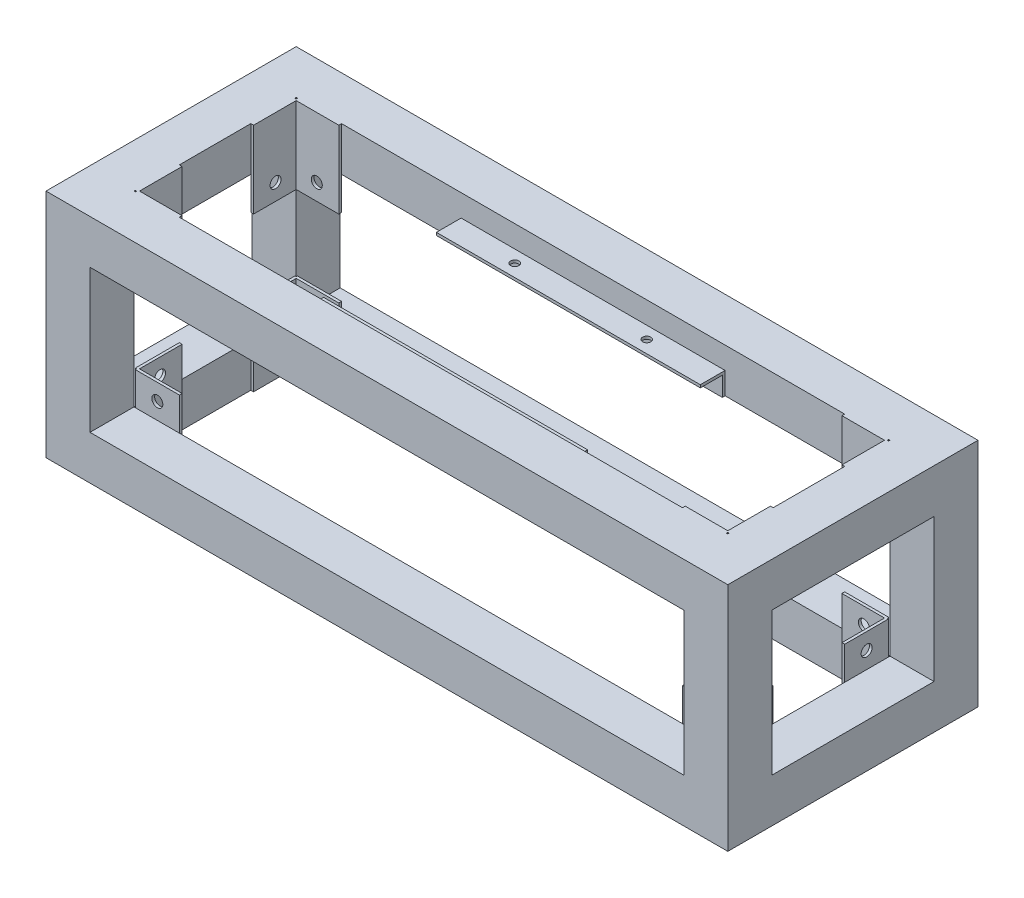
SolidWorks part; units mm, degrees
ref_plane "Front Plane" through (0, 0, 0) normal (0, 0, 1) x (1, 0, 0)
ref_plane "Top Plane" through (0, 0, 0) normal (0, 1, 0) x (1, 0, 0)
ref_plane "Right Plane" through (0, 0, 0) normal (1, 0, 0) x (0, 0, -1)
sketch "Sketch1" plane through (0, 0, 0) normal (0, 1, 0) x (1, 0, 0)
  line L1 (-196.85, 72.2313) -> (196.85, 72.2312)
  line L2 (-196.85, 72.2313) -> (-196.85, -72.2313)
  line L3 (-196.85, -72.2313) -> (196.85, -72.2313)
  line L4 (196.85, 72.2312) -> (196.85, -72.2313)
  line L5 (-196.85, 72.2313) -> (196.85, -72.2313) construction
  line L6 (-196.85, -72.2313) -> (196.85, 72.2312) construction
  point P0 (0, 0)
  dimension "D1" = 393.7
  dimension "D2" = 144.4625
extrude "Boss-Extrude1" add sketch "Sketch1" along normal blind 133.35
sketch "Sketch6" plane through (0, 0, 72.2313) normal (0, 0, 1) x (1, 0, 0)
  line L8 (-171.45, 25.4) -> (171.45, 25.4)
  line L9 (171.45, 25.4) -> (171.45, 107.95)
  line L10 (171.45, 107.95) -> (-171.45, 107.95)
  line L11 (-171.45, 107.95) -> (-171.45, 25.4)
  line L12 (-171.45, 25.4) -> (171.45, 25.4)
  line L13 (171.45, 25.4) -> (171.45, 107.95)
  line L14 (171.45, 107.95) -> (-171.45, 107.95)
  line L15 (-171.45, 107.95) -> (-171.45, 25.4)
  dimension "D1" = 25.4
extrude "Cut-Extrude4" cut sketch "Sketch6" against normal through all
sketch "Sketch7" plane through (-196.85, 0, 0) normal (-1, 0, 0) x (0, 0, 1)
  line L8 (-46.8312, 25.4) -> (46.8313, 25.4)
  line L9 (46.8313, 25.4) -> (46.8313, 107.95)
  line L10 (46.8313, 107.95) -> (-46.8312, 107.95)
  line L11 (-46.8312, 107.95) -> (-46.8312, 25.4)
  line L12 (-46.8312, 25.4) -> (46.8313, 25.4)
  line L13 (46.8313, 25.4) -> (46.8313, 107.95)
  line L14 (46.8313, 107.95) -> (-46.8312, 107.95)
  line L15 (-46.8312, 107.95) -> (-46.8312, 25.4)
  dimension "D1" = 25.4
extrude "Cut-Extrude5" cut sketch "Sketch7" against normal through all
sketch "Sketch8" plane through (0, 133.35, 0) normal (0, 1, 0) x (1, 0, 0)
  line L8 (171.45, -46.8313) -> (171.45, 46.8312)
  line L9 (171.45, 46.8312) -> (-171.45, 46.8312)
  line L10 (-171.45, 46.8312) -> (-171.45, -46.8313)
  line L11 (-171.45, -46.8313) -> (171.45, -46.8313)
  line L12 (171.45, -46.8313) -> (171.45, 46.8312)
  line L13 (171.45, 46.8312) -> (-171.45, 46.8312)
  line L14 (-171.45, 46.8312) -> (-171.45, -46.8313)
  line L15 (-171.45, -46.8313) -> (171.45, -46.8313)
  dimension "D1" = 25.4
extrude "Cut-Extrude6" cut sketch "Sketch8" against normal through all
ref_plane "Plane1" through (0, 66.675, 0) normal (0, 1, 0) x (1, 0, 0)
sketch "Sketch10" plane through (0, 0, 46.8313) normal (0, 0, -1) x (-1, 0, 0)
  line L0 (-171.45, 0) -> (-171.45, 25.4) construction
  line L1 (-170.6562, 0) -> (-145.2562, 0)
  line L2 (-170.6562, 0) -> (-170.6562, 44.45)
  line L3 (-170.6562, 44.45) -> (-145.2562, 44.45)
  line L4 (-145.2562, 0) -> (-145.2562, 44.45)
  line L5 (171.45, 0) -> (-171.45, 0) construction
  line L6 (0, 73.3425) -> (0, -73.3425) construction
  line L7 (145.2562, 0) -> (145.2562, 44.45)
  line L8 (170.6562, 44.45) -> (145.2562, 44.45)
  line L9 (170.6562, 0) -> (170.6562, 44.45)
  line L10 (170.6562, 0) -> (145.2562, 0)
  line L11 (79.4544, 66.675) -> (-79.4544, 66.675) construction
  line L12 (170.6562, 133.35) -> (145.2562, 133.35)
  line L13 (170.6562, 133.35) -> (170.6562, 88.9)
  line L14 (170.6562, 88.9) -> (145.2562, 88.9)
  line L15 (145.2562, 133.35) -> (145.2562, 88.9)
  line L16 (-145.2562, 133.35) -> (-145.2562, 88.9)
  line L17 (-170.6562, 88.9) -> (-145.2562, 88.9)
  line L18 (-170.6562, 133.35) -> (-170.6562, 88.9)
  line L19 (-170.6562, 133.35) -> (-145.2562, 133.35)
  circle A0 centre (-157.9563, 34.925) radius 3.175
  circle A1 centre (157.9563, 34.925) radius 3.175
  circle A2 centre (157.9563, 98.425) radius 3.175
  circle A3 centre (-157.9563, 98.425) radius 3.175
  point P5 (0, 0)
  point P12 (-157.9563, 44.45)
  dimension "D4" = 6.35
  dimension "D1" = 25.4
  dimension "D2" = 44.45
  dimension "D3" = 0.7937
  dimension "D5" = 9.525
extrude "Boss-Extrude7" add sketch "Sketch10" along normal blind 1.5875
mirror "Mirror5" about plane through (0, 0, 0) normal (0, 0, 1) of "Boss-Extrude7"
sketch "Sketch12" plane through (171.45, 0, 0) normal (-1, 0, 0) x (0, 0, 1)
  line L0 (46.8313, 0) -> (-46.8312, 0) construction
  line L1 (-46.0375, 0) -> (-20.6375, 0)
  line L2 (-46.0375, 0) -> (-46.0375, 44.45)
  line L3 (-46.0375, 44.45) -> (-20.6375, 44.45)
  line L4 (-20.6375, 0) -> (-20.6375, 44.45)
  line L5 (-46.8312, 0) -> (-46.8312, 25.4) construction
  line L6 (0, -73.3425) -> (0, 73.3425) construction
  line L7 (20.6375, 0) -> (20.6375, 44.45)
  line L8 (46.0375, 44.45) -> (20.6375, 44.45)
  line L9 (46.0375, 0) -> (46.0375, 44.45)
  line L10 (46.0375, 0) -> (20.6375, 0)
  line L11 (79.4544, 66.675) -> (-79.4544, 66.675) construction
  line L12 (46.0375, 133.35) -> (20.6375, 133.35)
  line L13 (46.0375, 133.35) -> (46.0375, 88.9)
  line L14 (46.0375, 88.9) -> (20.6375, 88.9)
  line L15 (20.6375, 133.35) -> (20.6375, 88.9)
  line L16 (-20.6375, 133.35) -> (-20.6375, 88.9)
  line L17 (-46.0375, 88.9) -> (-20.6375, 88.9)
  line L18 (-46.0375, 133.35) -> (-46.0375, 88.9)
  line L19 (-46.0375, 133.35) -> (-20.6375, 133.35)
  circle A0 centre (-33.3375, 34.925) radius 3.175
  circle A1 centre (33.3375, 34.925) radius 3.175
  circle A2 centre (33.3375, 98.425) radius 3.175
  circle A3 centre (-33.3375, 98.425) radius 3.175
  point P10 (0, 0)
  point P11 (-33.3375, 44.45)
  dimension "D5" = 6.35
  dimension "D1" = 0.7937
  dimension "D2" = 25.4
  dimension "D3" = 44.45
  dimension "D4" = 9.525
extrude "Boss-Extrude8" add sketch "Sketch12" along normal blind 1.5875
mirror "Mirror6" about plane through (0, 0, 0) normal (1, 0, 0) of "Boss-Extrude8"
sketch "Sketch13" plane through (0, 0, 46.8313) normal (0, 0, -1) x (-1, 0, 0)
  line L1 (-76.2, 107.95) -> (76.2, 107.95)
  line L2 (-76.2, 107.95) -> (-76.2, 120.65)
  line L3 (-76.2, 120.65) -> (76.2, 120.65)
  line L4 (76.2, 107.95) -> (76.2, 120.65)
  line L5 (145.2562, 133.35) -> (-145.2562, 133.35) construction
  line L6 (145.2562, 107.95) -> (76.2, 107.95) construction
  line L7 (145.2562, 107.95) -> (145.2562, 88.9) construction
  line L8 (145.2562, 107.95) -> (-145.2562, 107.95) construction
  line L9 (-76.2, 114.3) -> (-145.2562, 114.3) construction
  line L10 (-145.2562, 107.95) -> (-145.2562, 133.35) construction
  dimension "D1" = 12.7
  dimension "D2" = 12.7
  dimension "D3" = 152.4
extrude "Boss-Extrude9" add sketch "Sketch13" along normal blind 1.5875
sketch "Sketch14" plane through (0, 0, 45.2438) normal (0, 0, -1) x (-1, 0, 0)
  line L0 (-76.2, 120.65) -> (-76.2, 107.95) construction
  line L1 (-76.2, 120.65) -> (76.2, 120.65)
  line L2 (-76.2, 120.65) -> (-76.2, 119.0625)
  line L3 (-76.2, 119.0625) -> (76.2, 119.0625)
  line L4 (76.2, 120.65) -> (76.2, 119.0625)
  line L5 (76.2, 120.65) -> (-76.2, 120.65) construction
  line L6 (76.2, 107.95) -> (76.2, 120.65) construction
  dimension "D1" = 1.5875
extrude "Boss-Extrude10" add sketch "Sketch14" along normal blind 12.7
sketch "Sketch15" plane through (0, 120.65, 0) normal (0, 1, 0) x (1, 0, 0)
  line L0 (-76.2, -32.5438) -> (-76.2, -46.8313) construction
  line L1 (0, -73.3425) -> (0, 73.3425) construction
  circle A0 centre (-38.1, -39.6875) radius 2.3812
  circle A1 centre (38.1, -39.6875) radius 2.3812
  point P2 (0, 0)
  point P5 (-76.2, -39.6875)
  dimension "D2" = 4.7625
  dimension "D1" = 38.1
extrude "Cut-Extrude8" cut sketch "Sketch15" against normal up to next
mirror "Mirror7" about plane through (0, 0, 0) normal (0, 0, 1) of "Boss-Extrude9", "Boss-Extrude10", "Cut-Extrude8"
sketch "Sketch17" plane through (0, 0, -72.2313) normal (0, 0, -1) x (-1, 0, 0)
  line L0 (0, 25.4) -> (0, 0) construction
  line L1 (171.45, 25.4) -> (-171.45, 25.4) construction
  line L2 (-196.85, 0) -> (196.85, 0) construction
  line L3 (0, 12.7) -> (196.85, 12.7) construction
  line L4 (196.85, 133.35) -> (196.85, 0) construction
  circle A0 centre (69.85, 12.7) radius 3.175
  circle A1 centre (133.35, 12.7) radius 3.175
  point P14 (0, 0)
  point P15 (0, 0)
  dimension "D3" = 6.35
  dimension "D1" = 63.5
  dimension "D2" = 63.5
extrude "Cut-Extrude10" cut sketch "Sketch17" against normal up to next
equation "\"Steel thickness\"= .75in"
